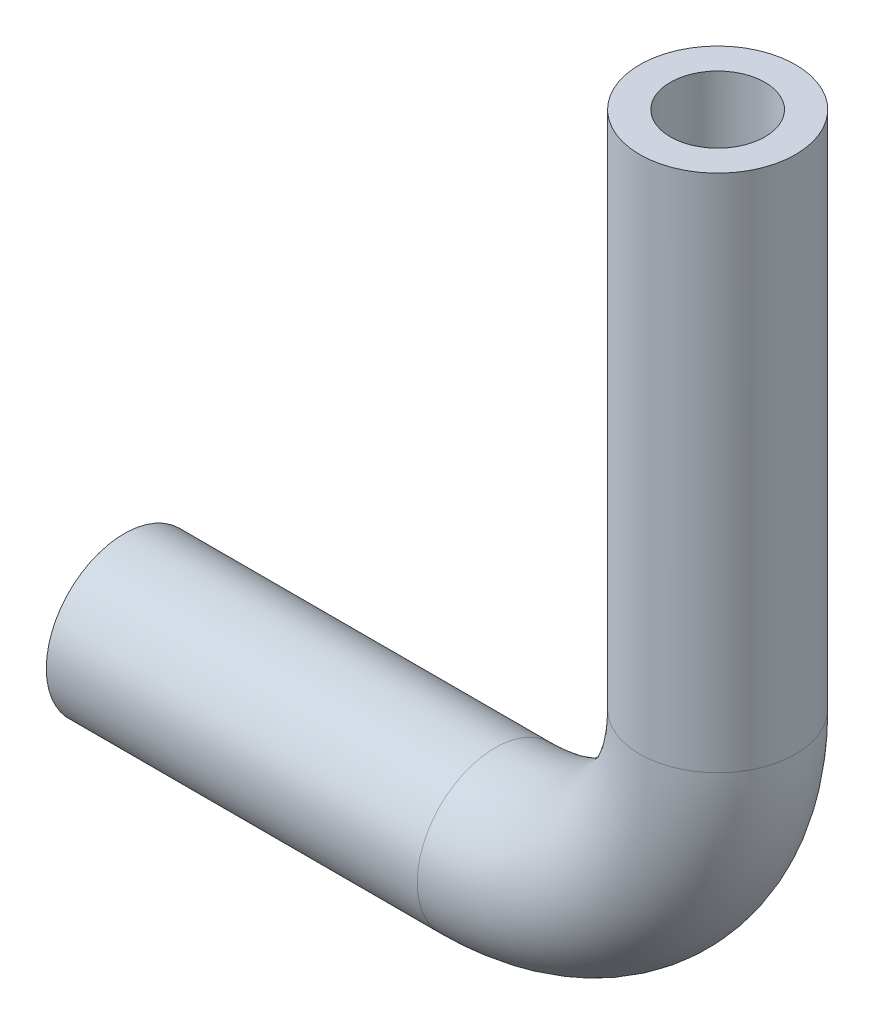
SolidWorks part; units mm, degrees
ref_plane "Ön Düzlem" through (0, 0, 0) normal (0, 0, 1) x (1, 0, 0)
ref_plane "Üst Düzlem" through (0, 0, 0) normal (0, 1, 0) x (1, 0, 0)
ref_plane "Sağ Düzlem" through (0, 0, 0) normal (1, 0, 0) x (0, 0, -1)
sketch "Sketch2" plane through (0, 0, 0) normal (0, 0, 1) x (1, 0, 0)
  line L0 (0, 0) -> (0, -70)
  line L1 (-30, -100) -> (-80, -100)
  arc A0 (0, -70) -> (-30, -100) centre (-30, -70) cw
  point P6 (0, -100)
  dimension "D3" = 30
  dimension "D1" = 100
  dimension "D2" = 80
sketch "Sketch3" plane through (0, 0, 0) normal (0, 1, 0) x (1, 0, 0)
  circle A0 centre (0, 0) radius 6.375
  circle A1 centre (0, 0) radius 10.5
  dimension "D1" = 12.75
  dimension "D2" = 21
sweep "Sweep1" add profiles "Sketch3" path "Sketch2"
